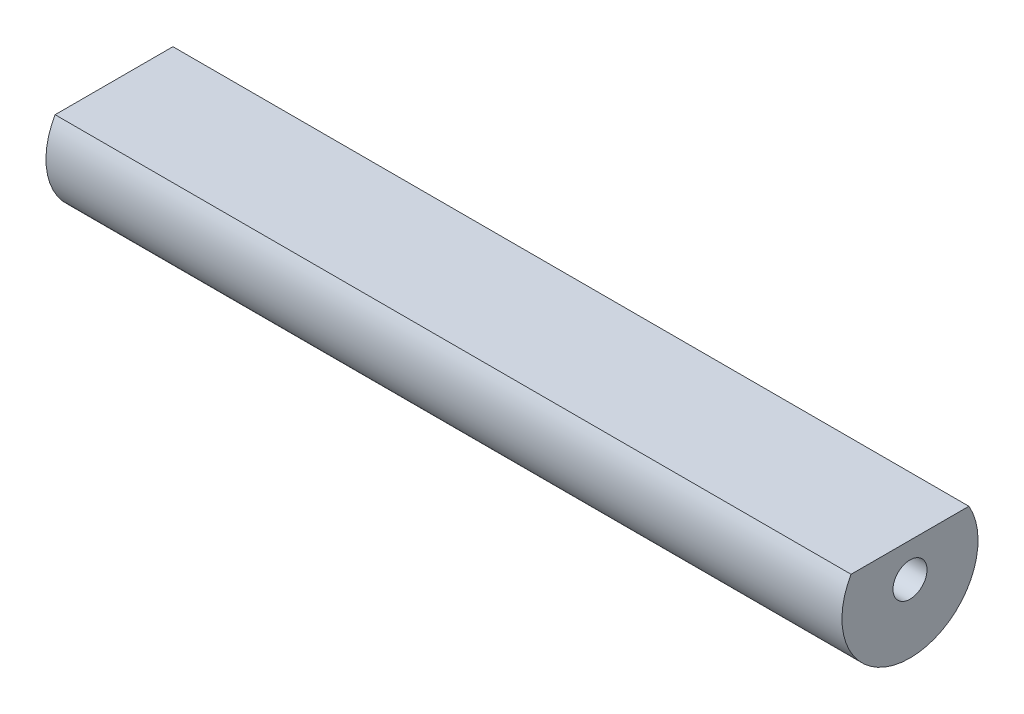
SolidWorks part; units mm, degrees
ref_plane "Plan de face" through (0, 0, 0) normal (0, 0, 1) x (1, 0, 0)
ref_plane "Plan de dessus" through (0, 0, 0) normal (0, 1, 0) x (1, 0, 0)
ref_plane "Plan de droite" through (0, 0, 0) normal (1, 0, 0) x (0, 0, -1)
sketch "Esquisse1" plane through (0, 0, 0) normal (0, 0, 1) x (1, 0, 0)
  line L1 (0, 0) -> (-117, 0)
  line L2 (0, 0) -> (0, 10)
  line L3 (0, 10) -> (-117, 10)
  line L4 (-117, 0) -> (-117, 10)
  dimension "D1" = 10
  dimension "D2" = 117
revolve "Révolution1" add sketch "Esquisse1" angle 360 about L1
sketch "Esquisse2" plane through (0, 0, 0) normal (1, 0, 0) x (0, 0, -1)
  circle A0 centre (0, 0) radius 2.5
  dimension "D1" = 5
extrude "Enlèv. mat.-Extru.1" cut sketch "Esquisse2" against normal up to next
sketch "Esquisse3" plane through (0, 0, 0) normal (1, 0, 0) x (0, 0, -1)
  line L1 (-10, 10) -> (10, 10)
  line L2 (-10, 10) -> (-10, 5)
  line L3 (-10, 5) -> (10, 5)
  line L4 (10, 10) -> (10, 5)
  circle A0 centre (0, 0) radius 10 construction
  dimension "D1" = 5
extrude "Enlèv. mat.-Extru.2" cut sketch "Esquisse3" against normal up to next
